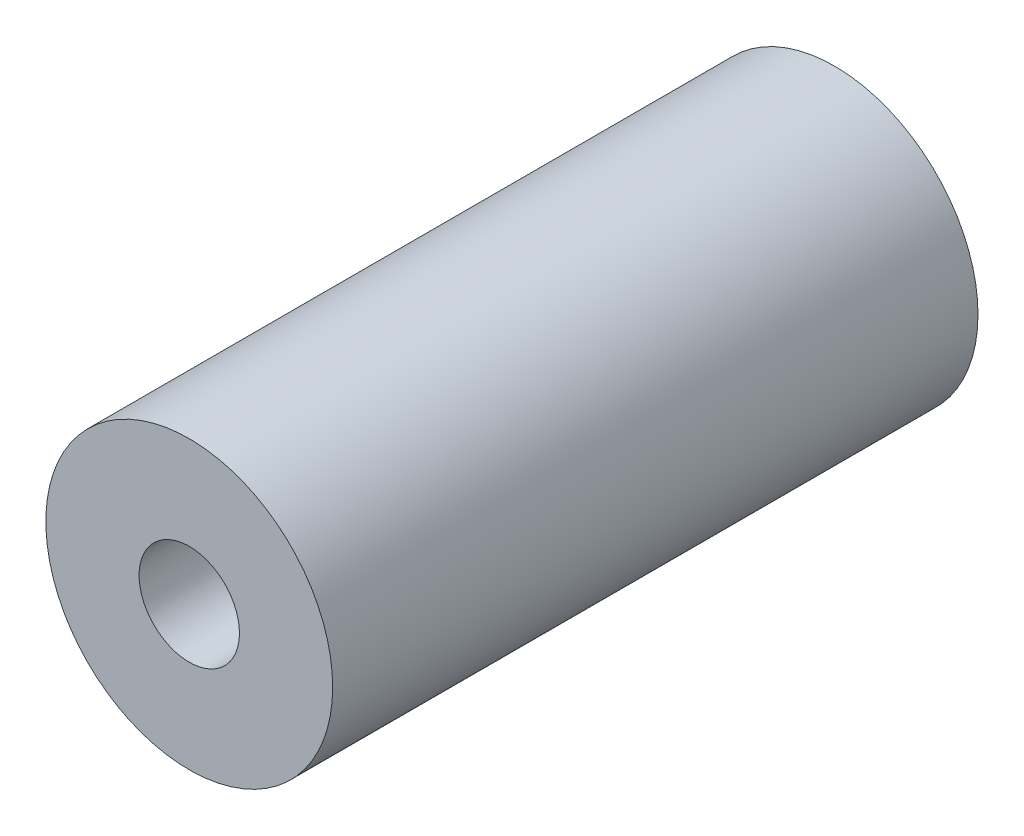
SolidWorks part; units mm, degrees
ref_plane "Front Plane" through (0, 0, 0) normal (0, 0, 1) x (1, 0, 0)
ref_plane "Top Plane" through (0, 0, 0) normal (0, 1, 0) x (1, 0, 0)
ref_plane "Right Plane" through (0, 0, 0) normal (1, 0, 0) x (0, 0, -1)
sketch "Sketch1" plane through (0, 0, 0) normal (0, 0, 1) x (1, 0, 0)
  circle A0 centre (0, 0) radius 4
  dimension "D1" = 8
extrude "Boss-Extrude1" add sketch "Sketch1" along normal blind 18
sketch "Sketch2" plane through (0, 0, 18) normal (0, 0, 1) x (1, 0, 0)
  circle A0 centre (0, 0) radius 1.4
  dimension "D1" = 2.8
extrude "Cut-Extrude1" cut sketch "Sketch2" against normal through all
